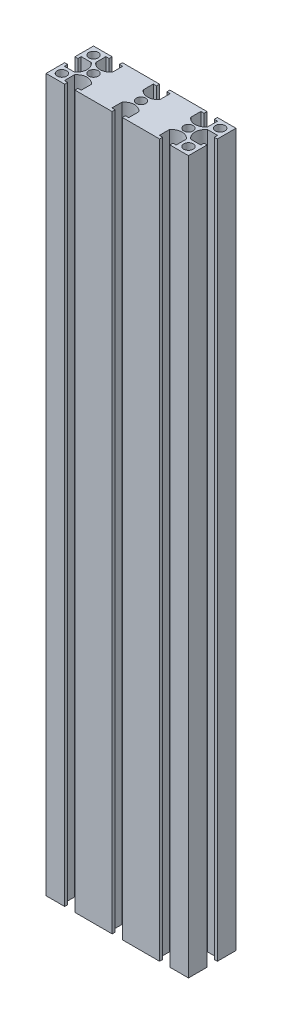
SolidWorks part; units mm, degrees
material "6061 合金"
ref_plane "前视基准面" through (0, 0, 0) normal (0, 0, 1) x (1, 0, 0)
ref_plane "上视基准面" through (0, 0, 0) normal (0, 1, 0) x (1, 0, 0)
ref_plane "右视基准面" through (0, 0, 0) normal (1, 0, 0) x (0, 0, -1)
other "Configuration Table"
sketch "草图1" plane through (0, 0, 0) normal (0, 1, 0) x (1, 0, 0)
  line L0 (0, 15) -> (0, 0) construction
  line L1 (-45, 15) -> (45, 15)
  line L2 (-45, 15) -> (-45, -15)
  line L3 (-45, -15) -> (45, -15)
  line L4 (45, 15) -> (45, -15)
  line L5 (-3.25, 15) -> (-3.25, 13.1)
  line L6 (-3.25, 13.1) -> (-5.3, 13.1)
  line L7 (-5.3, 13.1) -> (-5.3, 6.7467)
  line L8 (5.3, 13.1) -> (5.3, 6.7467)
  line L9 (3.25, 13.1) -> (5.3, 13.1)
  line L10 (3.25, 15) -> (3.25, 13.1)
  line L11 (0, 0) -> (45, 0) construction
  line L12 (3.25, -15) -> (3.25, -13.1)
  line L13 (3.25, -13.1) -> (5.3, -13.1)
  line L14 (5.3, -13.1) -> (5.3, -6.7467)
  line L15 (-5.3, -13.1) -> (-5.3, -6.7467)
  line L16 (-3.25, -13.1) -> (-5.3, -13.1)
  line L17 (-3.25, -15) -> (-3.25, -13.1)
  line L18 (26.75, 15) -> (26.75, 13.1)
  line L19 (26.75, 13.1) -> (24.7, 13.1)
  line L20 (24.7, 13.1) -> (24.7, 6.7467)
  line L21 (33.25, 15) -> (33.25, 13.1)
  line L22 (33.25, 13.1) -> (35.3, 13.1)
  line L23 (35.3, 13.1) -> (35.3, 6.7467)
  line L24 (43.1, -5.3) -> (36.7467, -5.3)
  line L25 (43.1, 5.3) -> (36.7467, 5.3)
  line L26 (45, 3.25) -> (43.1, 3.25)
  line L27 (43.1, 3.25) -> (43.1, 5.3)
  line L28 (45, -3.25) -> (43.1, -3.25)
  line L29 (43.1, -3.25) -> (43.1, -5.3)
  line L30 (24.7, -13.1) -> (24.7, -6.7467)
  line L31 (35.3, -13.1) -> (35.3, -6.7467)
  line L32 (33.25, -15) -> (33.25, -13.1)
  line L33 (33.25, -13.1) -> (35.3, -13.1)
  line L34 (26.75, -15) -> (26.75, -13.1)
  line L35 (26.75, -13.1) -> (24.7, -13.1)
  line L36 (16.9, 5.3) -> (23.2533, 5.3) [skipped]
  line L37 (16.9, -5.3) -> (23.2533, -5.3) [skipped]
  line L38 (15, -3.25) -> (16.9, -3.25) [skipped]
  line L39 (16.9, -3.25) -> (16.9, -5.3) [skipped]
  line L40 (15, 3.25) -> (16.9, 3.25) [skipped]
  line L41 (16.9, 3.25) -> (16.9, 5.3) [skipped]
  line L42 (-43.1, 3.25) -> (-43.1, 5.3)
  line L43 (-43.1, 5.3) -> (-36.7467, 5.3)
  line L44 (-45, -3.25) -> (-43.1, -3.25)
  line L45 (-43.1, -3.25) -> (-43.1, -5.3)
  line L46 (-43.1, -5.3) -> (-36.7467, -5.3)
  line L47 (-33.25, -13.1) -> (-35.3, -13.1)
  line L48 (-35.3, -13.1) -> (-35.3, -6.7467)
  line L49 (-33.25, -15) -> (-33.25, -13.1)
  line L50 (-26.75, -15) -> (-26.75, -13.1)
  line L51 (-26.75, -13.1) -> (-24.7, -13.1)
  line L52 (-24.7, -13.1) -> (-24.7, -6.7467)
  line L53 (-35.3, 13.1) -> (-35.3, 6.7467)
  line L54 (-33.25, 13.1) -> (-35.3, 13.1)
  line L55 (-33.25, 15) -> (-33.25, 13.1)
  line L56 (-26.75, 15) -> (-26.75, 13.1)
  line L57 (-26.75, 13.1) -> (-24.7, 13.1)
  line L58 (-24.7, 13.1) -> (-24.7, 6.7467)
  line L59 (-45, 3.25) -> (-43.1, 3.25)
  circle A0 centre (0, 0) radius 3
  arc A2 (-5.3, 6.7467) -> (5.3, 6.7467) centre (0, 10.73) ccw
  arc A3 (-5.3, -6.7467) -> (5.3, -6.7467) centre (0, -10.73) cw
  arc A4 (24.7, 6.7467) -> (35.3, 6.7467) centre (30, 10.73) ccw
  circle A5 centre (40, 10) radius 3
  arc A6 (36.7467, 5.3) -> (36.7467, -5.3) centre (40.73, 0) ccw
  arc A7 (35.3, -6.7467) -> (24.7, -6.7467) centre (30, -10.73) ccw
  arc A8 (23.2533, -5.3) -> (23.2533, 5.3) centre (19.27, 0) ccw [skipped]
  circle A9 centre (-40, 10) radius 3
  arc A10 (-36.7467, 5.3) -> (-36.7467, -5.3) centre (-40.73, 0) cw
  arc A11 (-35.3, -6.7467) -> (-24.7, -6.7467) centre (-30, -10.73) cw
  arc A12 (-24.7, 6.7467) -> (-35.3, 6.7467) centre (-30, 10.73) cw
  circle A13 centre (40, -10) radius 3
  circle A14 centre (-40, -10) radius 3
  circle A15 centre (30, 0) radius 3
  circle A16 centre (-30, 0) radius 3
  point P7 (45, 0)
  point P9 (0, 15)
  point P32 (-45, 3.25)
  point P41 (30, 0)
  point P42 (0, 4.1)
  point P74 (30, 0)
  dimension "D1" = 30
  dimension "D7" = 6.63
  dimension "D10" = 6
  dimension "D12" = 5
  dimension "D2" = 1.9
  dimension "D3" = 6.5
  dimension "D4" = 10.6
  dimension "D5" = 2
  dimension "D6" = 90
  dimension "D8" = 10.9
  dimension "D9" = 30
  dimension "D11" = 4
  dimension "D13" = 5
extrude "凸台-拉伸1" add sketch "草图1" along normal blind 450 contours L58 A12 L53 L54 L55 L1 L2 L59 L42 L43 A10 L46 L45 L44 L3 L49 L47 L48 A11 L52 L51 L50 L17 L16 L15 A3 L14 L13 L12 L34 L35 L30 A7 L31 L33 L32 L4 L28 L29 L24 A6 L25 L27 L26 L21
